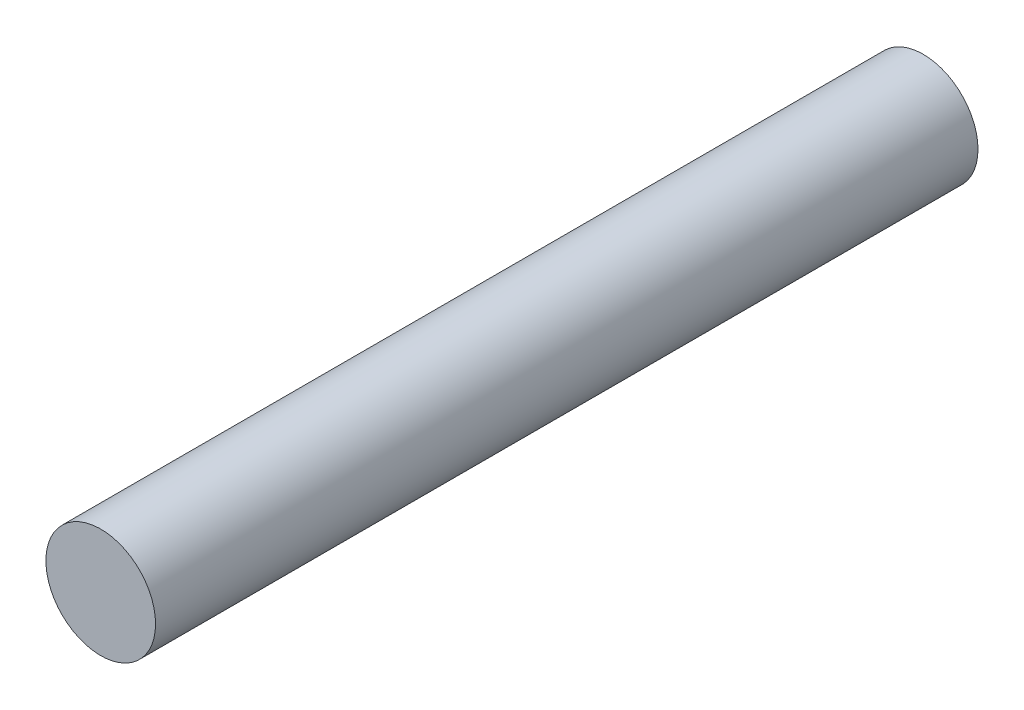
SolidWorks part; units mm, degrees
ref_plane "前视基准面" through (0, 0, 0) normal (0, 0, 1) x (1, 0, 0)
ref_plane "上视基准面" through (0, 0, 0) normal (0, 1, 0) x (1, 0, 0)
ref_plane "右视基准面" through (0, 0, 0) normal (1, 0, 0) x (0, 0, -1)
sketch "草图1" plane through (0, 0, 0) normal (0, 0, 1) x (1, 0, 0)
  circle A0 centre (0, 0) radius 2
extrude "凸台-拉伸1" add sketch "草图1" along normal blind 30
